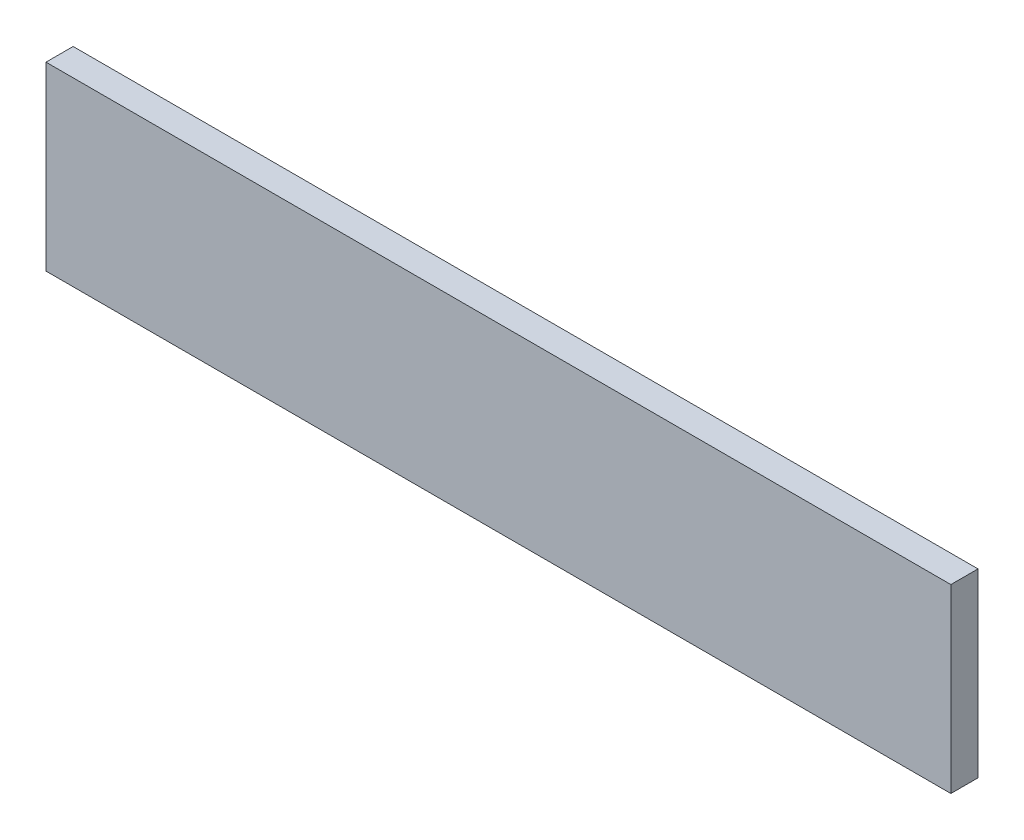
SolidWorks part; units mm, degrees
ref_plane "Alzado" through (0, 0, 0) normal (0, 0, 1) x (1, 0, 0)
ref_plane "Planta" through (0, 0, 0) normal (0, 1, 0) x (1, 0, 0)
ref_plane "Vista lateral" through (0, 0, 0) normal (1, 0, 0) x (0, 0, -1)
sketch "Croquis1" plane through (0, 0, 0) normal (0, 0, 1) x (1, 0, 0)
  line L1 (-100, -20) -> (100, -20)
  line L2 (-100, -20) -> (-100, 20)
  line L3 (-100, 20) -> (100, 20)
  line L4 (100, -20) -> (100, 20)
  line L5 (-100, -20) -> (100, 20) construction
  line L6 (-100, 20) -> (100, -20) construction
  point P0 (0, 0)
  dimension "D1" = 40
  dimension "D2" = 200
extrude "Saliente-Extruir1" add sketch "Croquis1" along normal blind 6
